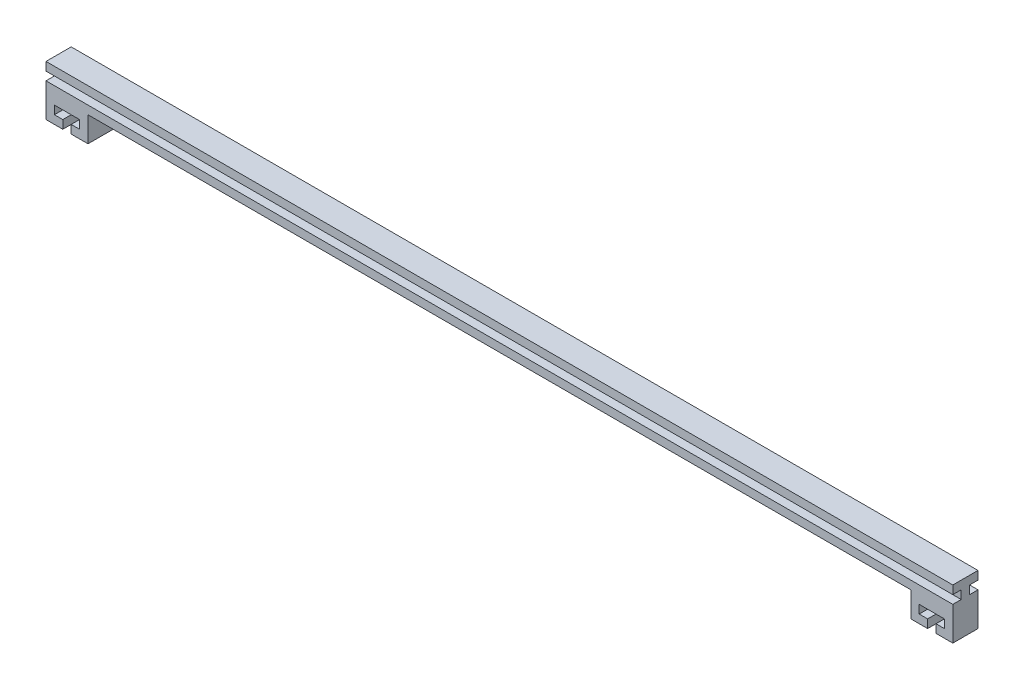
SolidWorks part; units mm, degrees
ref_plane "Front Plane" through (0, 0, 0) normal (0, 0, 1) x (1, 0, 0)
ref_plane "Top Plane" through (0, 0, 0) normal (0, 1, 0) x (1, 0, 0)
ref_plane "Right Plane" through (0, 0, 0) normal (1, 0, 0) x (0, 0, -1)
other "Center of Mass"
sketch "Sketch4" plane through (0, 0, 0) normal (0, 0, 1) x (1, 0, 0)
  line L0 (-2550, 50) -> (-2550, 100)
  line L1 (-2450, 50) -> (-2550, 50)
  line L2 (-2450, 50) -> (-2450, 200)
  line L3 (-2450, 200) -> (-2700, 200)
  line L4 (-2700, 50) -> (-2700, 200)
  line L5 (-2450, 50) -> (-2700, 200) construction
  line L6 (-2450, 200) -> (-2700, 50) construction
  line L7 (-2550, 100) -> (-2500, 100)
  line L8 (-2500, 100) -> (-2500, 150)
  line L9 (-2500, 150) -> (-2650, 150)
  line L10 (-2650, 150) -> (-2650, 100)
  line L11 (-2650, 100) -> (-2600, 100)
  line L12 (-2600, 100) -> (-2600, 50)
  line L13 (-2600, 50) -> (-2700, 50)
  line L14 (0, -55) -> (0, 55) construction
  line L15 (2450, 200) -> (2700, 50) construction
  line L16 (2450, 50) -> (2700, 200) construction
  line L17 (2600, 50) -> (2700, 50)
  line L18 (2600, 100) -> (2600, 50)
  line L19 (2650, 100) -> (2600, 100)
  line L20 (2650, 150) -> (2650, 100)
  line L21 (2500, 150) -> (2650, 150)
  line L22 (2500, 100) -> (2500, 150)
  line L23 (2550, 100) -> (2500, 100)
  line L24 (2700, 50) -> (2700, 200)
  line L25 (2450, 200) -> (2700, 200)
  line L26 (2450, 50) -> (2450, 200)
  line L27 (2450, 50) -> (2550, 50)
  line L28 (2550, 50) -> (2550, 100)
  point P0 (-2575, 125)
  point P14 (-2600, 75)
  point P29 (2575, 125)
  dimension "D1" = 250
  dimension "D2" = 150
  dimension "D3" = 50
  dimension "D4" = 100
  dimension "D5" = 100
  dimension "D6" = 50
  dimension "D7" = 50
  dimension "D8" = 50
  dimension "D9" = 100
  dimension "D10" = 2450
  dimension "D11" = 50
extrude "Boss-Extrude1" add sketch "Sketch4" along normal blind 150
ref_plane "Plane1" through (-2700, 0, 0) normal (-1, 0, 0) x (0, 0, 1)
sketch "Sketch5" plane through (-2700, 0, 0) normal (-1, 0, 0) x (0, 0, 1)
  line L0 (0, 200) -> (150, 200)
  line L1 (150, 200) -> (150, 250)
  line L2 (150, 250) -> (100, 250)
  line L3 (100, 250) -> (100, 300)
  line L4 (100, 300) -> (150, 300)
  line L5 (150, 300) -> (150, 350)
  line L6 (150, 350) -> (0, 350)
  line L7 (0, 350) -> (0, 300)
  line L8 (0, 300) -> (50, 300)
  line L9 (50, 300) -> (50, 250)
  line L10 (50, 250) -> (0, 250)
  line L11 (0, 250) -> (0, 200)
  dimension "D1" = 150
  dimension "D2" = 50
  dimension "D3" = 50
  dimension "D4" = 150
  dimension "D5" = 50
  dimension "D6" = 50
  dimension "D7" = 50
  dimension "D8" = 50
extrude "Boss-Extrude2" add sketch "Sketch5" against normal blind 5400
